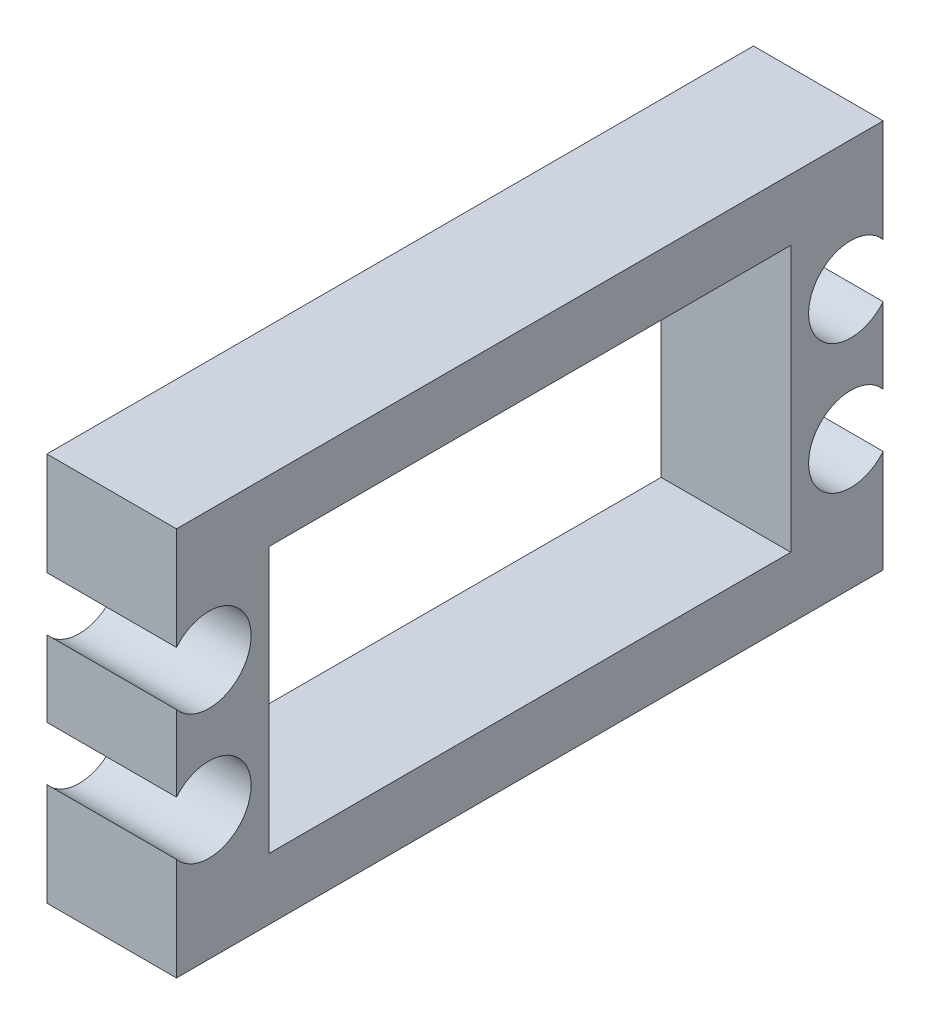
SolidWorks part; units mm, degrees
ref_plane "Front Plane" through (0, 0, 0) normal (0, 0, 1) x (1, 0, 0)
ref_plane "Top Plane" through (0, 0, 0) normal (0, 1, 0) x (1, 0, 0)
ref_plane "Right Plane" through (0, 0, 0) normal (1, 0, 0) x (0, 0, -1)
sketch "Sketch1" plane through (0, 0, 0) normal (1, 0, 0) x (0, 0, -1)
  line L1 (-27.25, 25.75) -> (27.25, 25.75)
  line L2 (-27.25, 25.75) -> (-27.25, -4.25)
  line L3 (-27.25, -4.25) -> (27.25, -4.25)
  line L4 (27.25, 25.75) -> (27.25, -4.25)
  line L7 (-20.125, 21) -> (20.125, 21)
  line L8 (-20.125, 21) -> (-20.125, 0.5)
  line L10 (20.125, 21) -> (20.125, 0.5)
  line L13 (-20.125, 0.5) -> (20.125, 0.5)
  line L20 (-20.125, 10.75) -> (20.125, 10.75) construction
  line L21 (0, 21) -> (0, 0.5) construction
  point P0 (0, 0)
  point P5 (0, 0)
  point P11 (0, 0)
  dimension "D1" = 54.5
  dimension "D2" = 30
  dimension "D3" = 40.25
  dimension "D4" = 20.5
  dimension "D5" = 4.75
extrude "Boss-Extrude1" add sketch "Sketch1" along normal blind 10
sketch "Sketch3" plane through (10, 0, 0) normal (1, 0, 0) x (0, 0, -1)
  line L0 (-20.125, 10.75) -> (20.125, 10.75) construction
  line L1 (-20.125, 21) -> (-20.125, 0.5) construction
  line L2 (20.125, 0.5) -> (20.125, 21) construction
  line L3 (0, 0.5) -> (0, 21) construction
  line L4 (-20.125, 0.5) -> (20.125, 0.5) construction
  line L5 (20.125, 21) -> (-20.125, 21) construction
  line L6 (-27.25, 10.75) -> (27.25, 10.75) construction
  line L7 (-27.25, 25.75) -> (-27.25, -4.25) construction
  line L8 (27.25, -4.25) -> (27.25, 25.75) construction
  line L9 (-27.25, 17.8267) -> (-27.25, 13.6733)
  line L10 (27.25, 17.8267) -> (27.25, 13.6733)
  line L11 (27.25, 3.6733) -> (27.25, 7.8267)
  line L12 (-27.25, 3.6733) -> (-27.25, 7.8267)
  arc A0 (-27.25, 13.6733) -> (-27.25, 17.8267) centre (-24.75, 15.75) ccw
  arc A1 (27.25, 13.6733) -> (27.25, 17.8267) centre (24.75, 15.75) cw
  arc A2 (27.25, 7.8267) -> (27.25, 3.6733) centre (24.75, 5.75) ccw
  arc A3 (-27.25, 7.8267) -> (-27.25, 3.6733) centre (-24.75, 5.75) cw
  dimension "D1" = 6.5
  dimension "D2" = 4.625
  dimension "D3" = 5.25
extrude "Cut-Extrude1" cut sketch "Sketch3" against normal blind 20
